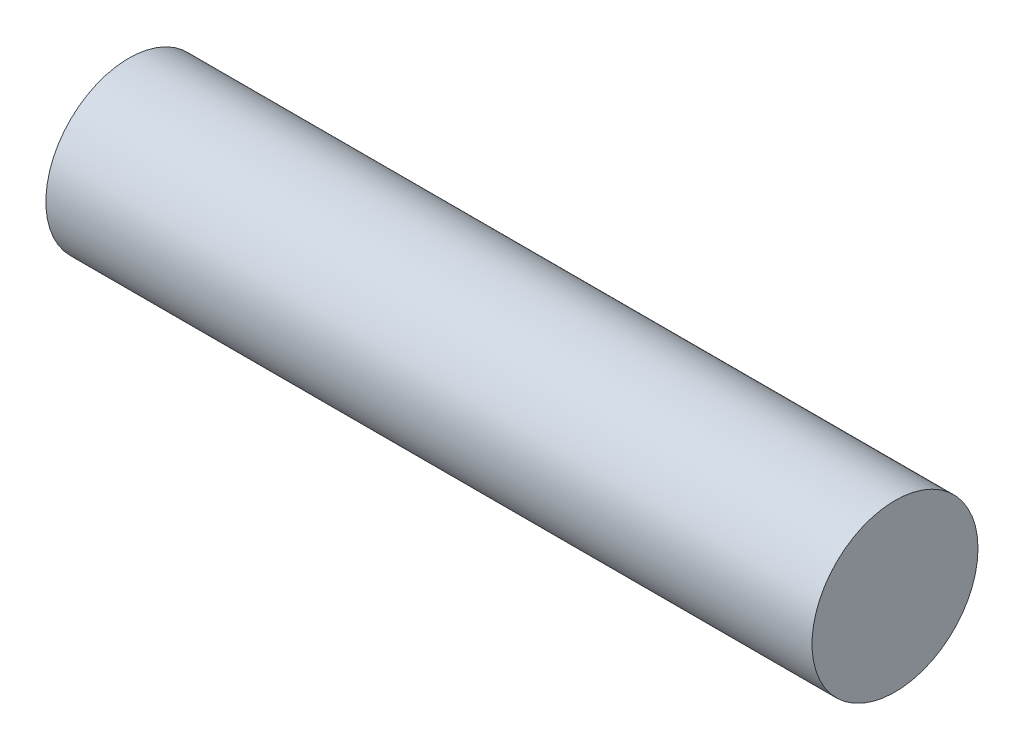
SolidWorks part; units mm, degrees
ref_plane "Front Plane" through (0, 0, 0) normal (0, 0, 1) x (1, 0, 0)
ref_plane "Top Plane" through (0, 0, 0) normal (0, 1, 0) x (1, 0, 0)
ref_plane "Right Plane" through (0, 0, 0) normal (1, 0, 0) x (0, 0, -1)
sketch "Sketch1" plane through (0, 0, 0) normal (1, 0, 0) x (0, 0, -1)
  line L0 (-0.3286, 0.811) -> (7.6046, 4.025)
  line L1 (7.6046, 4.025) -> (17.0617, 7.8564)
  line L2 (17.3902, 7.9204) -> (20.8459, 7.9204)
  line L3 (21.1314, 7.8725) -> (24.6264, 6.6662)
  line L4 (24.6101, 6.6716) -> (28.4424, 5.4327)
  line L5 (24.8839, 5.4239) -> (31.1549, 2.8249) construction
  circle A0 centre (0, 0) radius 0.875
  circle A1 centre (7.9331, 3.214) radius 0.875
  circle A2 centre (17.3902, 7.0454) radius 0.875
  circle A3 centre (20.8459, 7.0454) radius 0.875
  arc A4 (24.6101, 6.6716) -> (24.6264, 6.6662) centre (24.341, 5.8391) ccw
  arc A5 (29.2896, 3.5979) -> (28.4424, 5.4327) centre (28.0194, 4.1244) ccw
  point P10 (20.7169, 7.0454)
  point P12 (24.341, 5.8391)
  point P28 (28.0194, 4.1244)
  dimension "D1" = 2.75
  dimension "D2" = 1.75
sketch "Sketch2" plane through (0, 0, 0) normal (1, 0, 0) x (0, 0, -1)
  circle A0 centre (7.1521, 13.5854) radius 1.0831
extrude "Boss-Extrude1" add sketch "Sketch2" along normal blind 10
